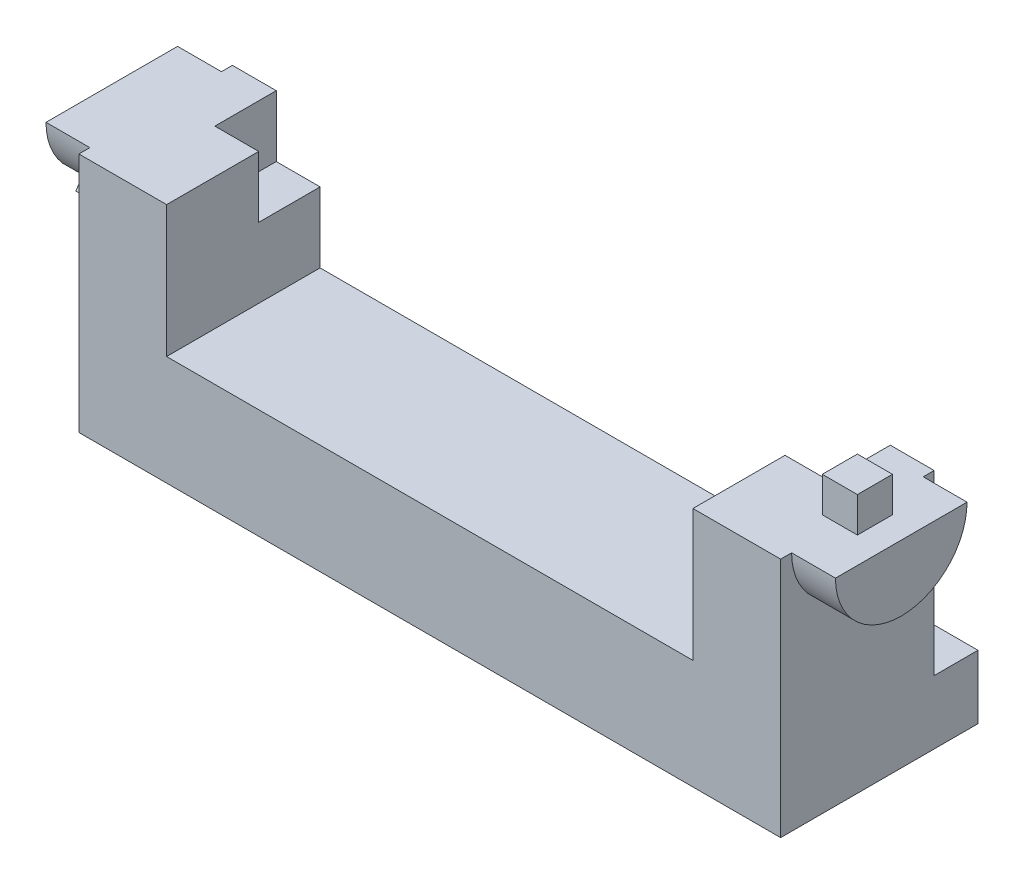
SolidWorks part; units mm, degrees
ref_plane "Front Plane" through (0, 0, 0) normal (0, 0, 1) x (1, 0, 0)
ref_plane "Top Plane" through (0, 0, 0) normal (0, 1, 0) x (1, 0, 0)
ref_plane "Right Plane" through (0, 0, 0) normal (1, 0, 0) x (0, 0, -1)
sketch "Sketch1" plane through (0, 0, 0) normal (0, 0, 1) x (1, 0, 0)
  line L1 (0, 0) -> (40.64, 0)
  line L2 (0, 0) -> (0, 6.35)
  line L3 (0, 6.35) -> (40.64, 6.35)
  line L4 (40.64, 0) -> (40.64, 6.35)
  dimension "D1" = 40.64
  dimension "D2" = 6.35
extrude "Boss-Extrude1" add sketch "Sketch1" along normal blind 8.89
sketch "Sketch2" plane through (0, 6.35, 0) normal (0, 1, 0) x (1, 0, 0)
  line L0 (0, -8.89) -> (0, 0) construction
  line L1 (0, -8.89) -> (5.08, -8.89)
  line L2 (0, -8.89) -> (0, 0)
  line L3 (0, 0) -> (5.08, 0)
  line L4 (5.08, -8.89) -> (5.08, 0)
  line L5 (40.64, -8.89) -> (0, -8.89) construction
  line L6 (40.64, 0) -> (0, 0) construction
  dimension "D1" = 5.08
extrude "Boss-Extrude2" add sketch "Sketch2" along normal blind 7.62
sketch "Sketch3" plane through (0, 6.35, 0) normal (0, 1, 0) x (1, 0, 0)
  line L0 (40.64, 0) -> (5.08, 0) construction
  line L1 (40.64, -8.89) -> (35.56, -8.89)
  line L2 (40.64, -8.89) -> (40.64, 0)
  line L3 (40.64, 0) -> (35.56, 0)
  line L4 (35.56, -8.89) -> (35.56, 0)
  dimension "D1" = 5.08
extrude "Boss-Extrude3" add sketch "Sketch3" along normal blind 7.62
sketch "Sketch4" plane through (5.08, 0, 0) normal (1, 0, 0) x (0, 0, -1)
  line L1 (0, 13.97) -> (-3.556, 13.97)
  line L2 (0, 13.97) -> (0, 10.414)
  line L3 (0, 10.414) -> (-3.556, 10.414)
  line L4 (-3.556, 13.97) -> (-3.556, 10.414)
  dimension "D1" = 3.556
  dimension "D2" = 3.556
extrude "Cut-Extrude1" cut sketch "Sketch4" against normal blind 2.54
sketch "Sketch5" plane through (0, 0, 0) normal (-1, 0, 0) x (0, 0, 1)
  line L0 (0, 13.97) -> (8.89, 13.97) construction
  line L1 (8.255, 13.97) -> (0.635, 13.97)
  arc A0 (8.255, 13.97) -> (0.635, 13.97) centre (4.445, 13.97) cw
  dimension "D1" = 7.62
extrude "Boss-Extrude4" add sketch "Sketch5" along normal blind 2.54
sketch "Sketch6" plane through (0, 0, 0) normal (0, 0, -1) x (-1, 0, 0)
  line L0 (-40.64, 0) -> (-40.64, 13.97) construction
  line L1 (0, 0) -> (-40.64, 0)
  line L2 (0, 0) -> (0, 3.683)
  line L3 (0, 3.683) -> (-40.64, 3.683)
  line L4 (-40.64, 0) -> (-40.64, 3.683)
  line L5 (-20.32, 3.683) -> (-20.32, 6.35) construction
  line L6 (-35.56, 6.35) -> (-5.08, 6.35) construction
  dimension "D1" = 2.667
extrude "Boss-Extrude5" add sketch "Sketch6" along normal blind 2.54
sketch "Sketch7" plane through (35.56, 0, 0) normal (-1, 0, 0) x (0, 0, 1)
  line L1 (0, 13.97) -> (3.556, 13.97)
  line L2 (0, 13.97) -> (0, 9.398)
  line L3 (0, 9.398) -> (3.556, 9.398)
  line L4 (3.556, 13.97) -> (3.556, 9.398)
  dimension "D1" = 3.556
  dimension "D2" = 4.572
extrude "Cut-Extrude2" cut sketch "Sketch7" against normal blind 2.54
sketch "Sketch8" plane through (40.64, 0, 0) normal (1, 0, 0) x (0, 0, -1)
  line L0 (-8.89, 13.97) -> (0, 13.97) construction
  line L1 (-0.635, 13.97) -> (-8.255, 13.97)
  arc A0 (-8.255, 13.97) -> (-0.635, 13.97) centre (-4.445, 13.97) ccw
  dimension "D1" = 7.62
extrude "Boss-Extrude6" add sketch "Sketch8" along normal blind 2.54
ref_plane "Plane1" through (0, 0, 0) normal (0, 1, 0) x (1, 0, 0)
sketch "Sketch10" plane through (0, 0, 0) normal (0, 1, 0) x (1, 0, 0)
  line L0 (-2.54, -0.635) -> (-2.54, -8.255) construction
  line L1 (-1.905, -1.796) -> (-0.889, -1.796)
  line L2 (-1.905, -1.796) -> (-1.905, -6.876)
  line L3 (-1.905, -6.876) -> (-0.889, -6.876)
  line L4 (-0.889, -1.796) -> (-0.889, -6.876)
  point P4 (-1.397, -6.876)
  dimension "D1" = 5.08
  dimension "D2" = 1.016
  dimension "D3" = 0.635
wrap "Wrap2" sketch "Sketch10" wrap type emboss source sketch "Sketch10" thickness 0.762 face at (-1.27, 12.065, 4.445) parameters "D1"=0.762
sketch "Sketch11" plane through (0, 0, 0) normal (0, -1, 0) x (1, 0, 0)
  line L0 (20.32, -2.54) -> (20.32, 3.81) construction
  line L1 (40.64, -2.54) -> (0, -2.54) construction
  line L3 (20.574, -2.54) -> (20.066, -2.54)
  line L4 (20.574, -2.54) -> (20.574, 3.81)
  line L5 (20.574, 3.81) -> (20.066, 3.81)
  line L6 (20.066, -2.54) -> (20.066, 3.81)
  dimension "D1" = 6.35
  dimension "D2" = 0.254
  dimension "D3" = 0.254
extrude "Cut-Extrude3" cut sketch "Sketch11" against normal blind 1.27
sketch "Sketch12" plane through (0, 13.97, 0) normal (0, 1, 0) x (1, 0, 0)
  line L0 (43.18, -0.635) -> (43.18, -8.255) construction
  line L1 (41.656, -3.429) -> (39.624, -3.429)
  line L2 (41.656, -3.429) -> (41.656, -5.461)
  line L3 (41.656, -5.461) -> (39.624, -5.461)
  line L4 (39.624, -3.429) -> (39.624, -5.461)
  line L5 (43.18, -0.635) -> (40.64, -0.635) construction
  dimension "D1" = 2.032
  dimension "D2" = 2.032
  dimension "D3" = 1.524
  dimension "D4" = 2.794
extrude "Boss-Extrude7" add sketch "Sketch12" along normal blind 2.032
